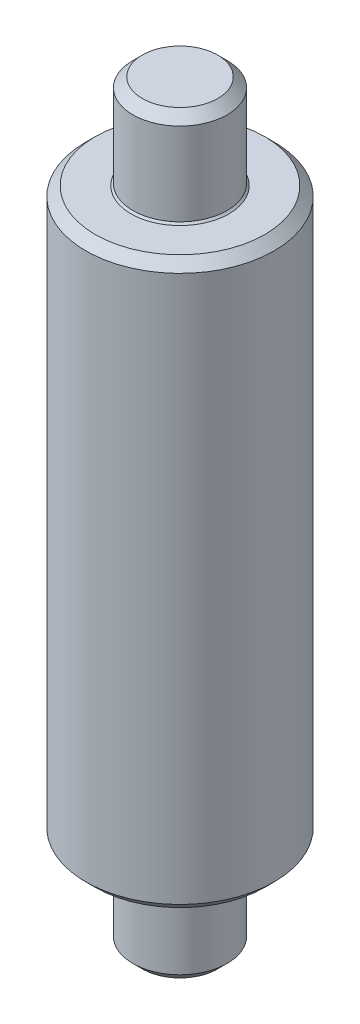
SolidWorks part; units mm, degrees
ref_plane "前视基准面" through (0, 0, 0) normal (0, 0, 1) x (1, 0, 0)
ref_plane "上视基准面" through (0, 0, 0) normal (0, 1, 0) x (1, 0, 0)
ref_plane "右视基准面" through (0, 0, 0) normal (1, 0, 0) x (0, 0, -1)
other "Configuration Table"
sketch "草图1" plane through (0, 0, 0) normal (0, 0, 1) x (1, 0, 0)
  line L0 (0, 17.9143) -> (0, -10.0949) construction
  line L1 (0, 40) -> (5, 40)
  line L2 (5, 40) -> (5, 30)
  line L3 (5, 30) -> (10, 30)
  line L4 (10, 30) -> (10, -30)
  line L5 (10, -30) -> (5, -30)
  line L6 (5, -30) -> (5, -40)
  line L7 (5, -40) -> (0, -40)
  line L8 (0, 0) -> (25.4592, 0) construction
  line L9 (0, 40) -> (0, -40)
  dimension "D1" = 5
  dimension "D2" = 10
  dimension "D3" = 60
  dimension "D4" = 10
  dimension "D5" = 10
revolve "旋转1" add sketch "草图1" angle 360 about L9
chamfer "倒角1" distance 1 angle 45 4 edges at (-10, -30, 0) (-10, 30, 0) (-5, -40, 0) (-5, 40, 0)
chamfer "倒角2" distance 0.2 angle 45 2 edges at (-5, 30, 0) (-5, -30, 0)
